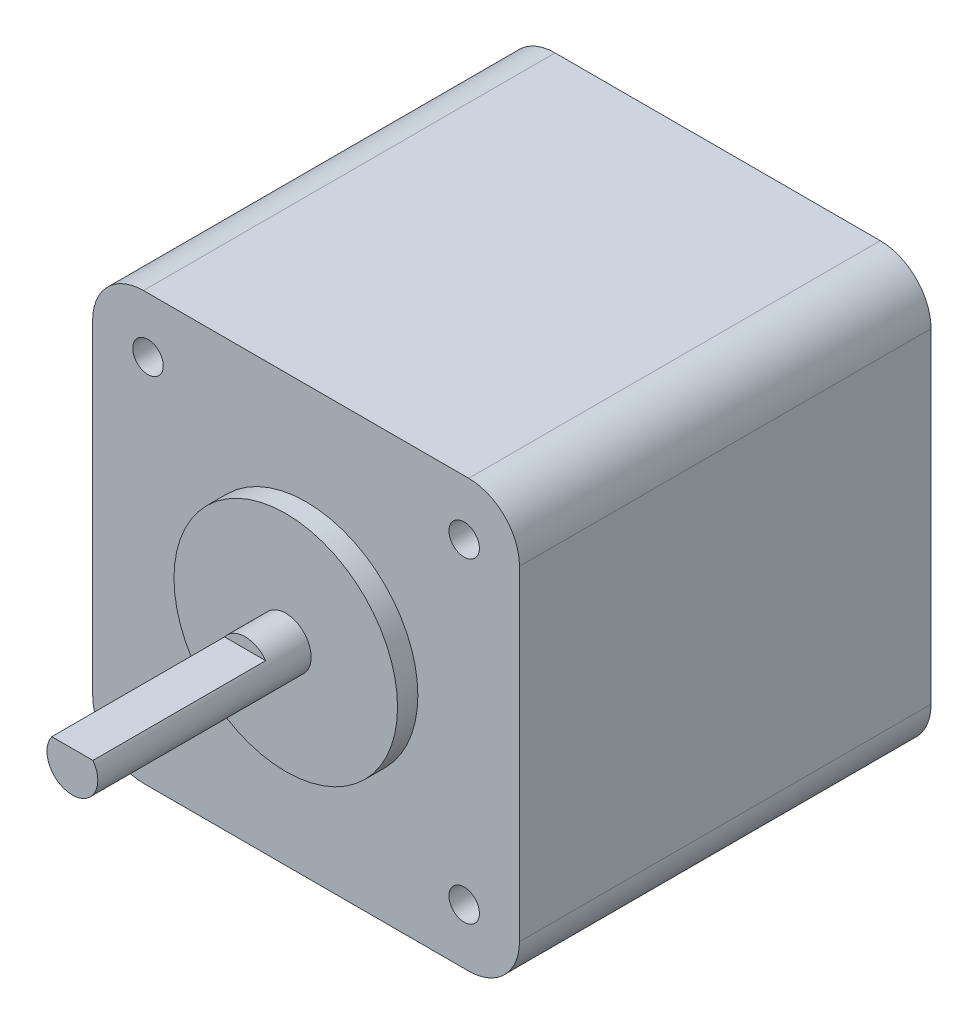
SolidWorks part; units mm, degrees
ref_plane "Front Plane" through (0, 0, 0) normal (0, 0, 1) x (1, 0, 0)
ref_plane "Top Plane" through (0, 0, 0) normal (0, 1, 0) x (1, 0, 0)
ref_plane "Right Plane" through (0, 0, 0) normal (1, 0, 0) x (0, 0, -1)
sketch "Sketch1" plane through (0, 0, 0) normal (0, 0, 1) x (1, 0, 0)
  line L1 (-21, -21) -> (21, -21)
  line L2 (-21, -21) -> (-21, 21)
  line L3 (-21, 21) -> (21, 21)
  line L4 (21, -21) -> (21, 21)
  line L5 (-21, -21) -> (21, 21) construction
  line L6 (-21, 21) -> (21, -21) construction
  point P0 (0, 0)
  dimension "D1" = 42
  dimension "D2" = 42
extrude "Boss-Extrude1" add sketch "Sketch1" along normal blind 40.5
sketch "Sketch2" plane through (0, 0, 40.5) normal (0, 0, 1) x (1, 0, 0)
  circle A0 centre (0, 0) radius 11
  dimension "D1" = 22
extrude "Boss-Extrude2" add sketch "Sketch2" along normal blind 2
sketch "Sketch3" plane through (0, 0, 42.5) normal (0, 0, 1) x (1, 0, 0)
  circle A0 centre (0, 0) radius 2.5
  dimension "D1" = 5
extrude "Boss-Extrude3" add sketch "Sketch3" along normal blind 21
fillet "Fillet1" radius 5 4 edges at (-21, -21, 20.25) (21, -21, 20.25) (21, 21, 20.25) (-21, 21, 20.25)
sketch "Sketch4" plane through (0, 0, 40.5) normal (0, 0, 1) x (1, 0, 0)
  line L0 (0, 24.4175) -> (0, -23.581) construction
  line L1 (-26.2834, 26.2834) -> (0, 0) construction
  line L2 (0, 0) -> (26.0676, -26.0676) construction
  line L3 (31.8188, 31.8188) -> (0, 0) construction
  line L4 (0, 0) -> (-31.0526, -31.0526) construction
  circle A0 centre (15.5563, 15.5563) radius 1.5
  circle A1 centre (-15.5563, -15.5563) radius 1.5
  circle A2 centre (15.5563, -15.5563) radius 1.5
  circle A3 centre (-15.5563, 15.5563) radius 1.5
  dimension "D3" = 22
  dimension "D4" = 22
  dimension "D5" = 22
  dimension "D7" = 3
  dimension "D1" = 45
  dimension "D2" = 45
  dimension "D6" = 22
extrude "Cut-Extrude1" cut sketch "Sketch4" against normal blind 10
sketch "Sketch5" plane through (0, 0, 63.5) normal (0, 0, 1) x (1, 0, 0)
  line L0 (-2.0247, 1.4665) -> (2.0247, 1.4665)
  circle A0 centre (0, 0) radius 2.5 construction
  circle A1 centre (0, 0) radius 2.5 construction
  arc A2 (2.0247, 1.4665) -> (-2.0247, 1.4665) centre (0, 0) ccw
extrude "Cut-Extrude2" cut sketch "Sketch5" against normal blind 17
